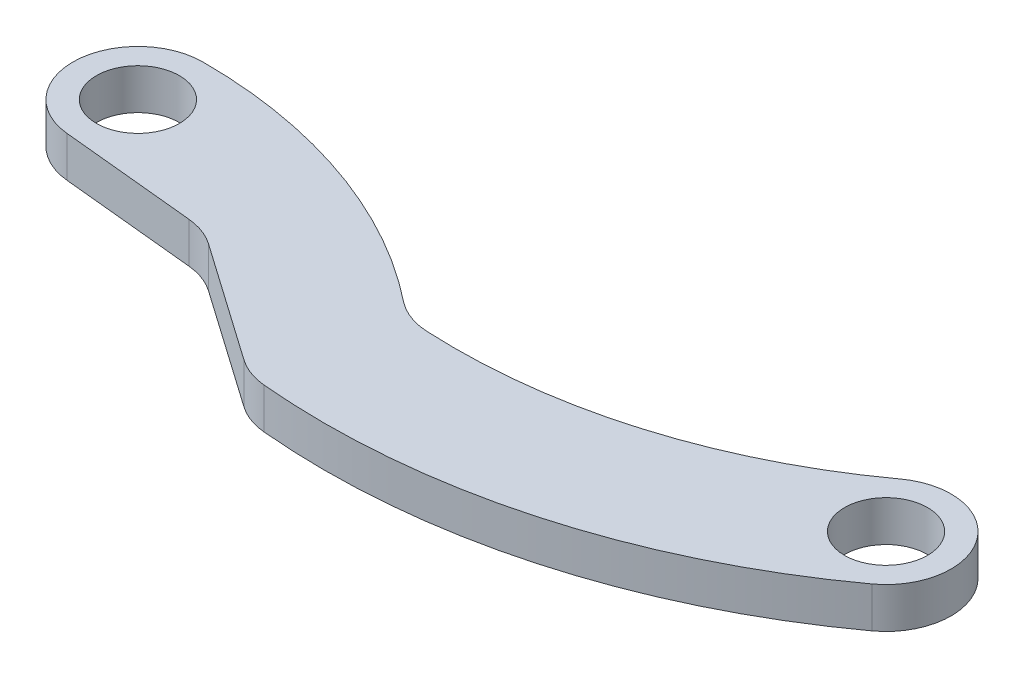
SolidWorks part; units mm, degrees
material "Thornel Mat VMA"
ref_plane "前视基准面" through (0, 0, 0) normal (0, 0, 1) x (1, 0, 0)
ref_plane "上视基准面" through (0, 0, 0) normal (0, 1, 0) x (1, 0, 0)
ref_plane "右视基准面" through (0, 0, 0) normal (1, 0, 0) x (0, 0, -1)
sketch "草图1" plane through (0, 0, 0) normal (0, 1, 0) x (1, 0, 0)
  line L0 (0, 0) -> (92, 0) construction
  line L1 (-0.7879, -7.9611) -> (17.9823, -9.8187)
  line L2 (17.9823, -9.8187) -> (35.9824, -22.4225)
  line L5 (92, 0) -> (63.0356, -41.3654) construction
  circle A2 centre (0, 0) radius 5.1
  circle A3 centre (92, 0) radius 5.1
  arc A4 (39.7162, -6.7253) -> (87.2821, 6.4607) centre (46, 62.9921) ccw
  arc A5 (96.7179, -6.4607) -> (35.9824, -22.4225) centre (46, 62.9921) cw
  arc A6 (0, 8) -> (-0.7879, -7.9611) centre (0, 0) ccw
  arc A7 (96.7179, -6.4607) -> (87.2821, 6.4607) centre (92, 0) ccw
  arc A8 (0, 8) -> (39.7162, -6.7253) centre (0, -52.9226) cw
  point P1 (59.3213, -27.2323)
  point P12 (48.9076, -16.3409)
  point P14 (33.2898, -5.8444)
  point P16 (39.7162, -6.4607)
  point P17 (39.7162, -6.4607)
  point P19 (-2.0432, 7.7347)
  point P20 (0, 0)
  dimension "D2" = 8
  dimension "D3" = 10.2
  dimension "D4" = 10.2
  dimension "D5" = 70
  dimension "D9" = 15
  dimension "D1" = 92
  dimension "D6" = 35
  dimension "D7" = 55
  dimension "D8" = 50.4978
extrude "凸台-拉伸1" add sketch "草图1" along normal blind 5
fillet "圆角1" radius 8 3 edges at (39.7162, 2.5, 6.7253) (35.9824, 2.5, 22.4225) (17.9823, 2.5, 9.8187)
